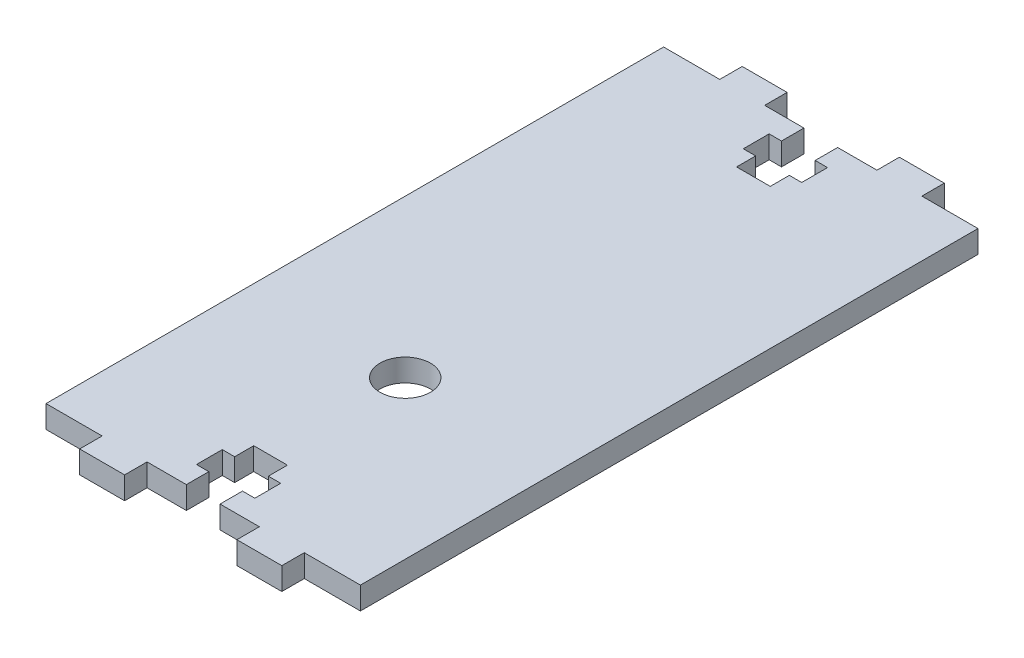
SolidWorks part; units mm, degrees
ref_plane "Front Plane" through (0, 0, 0) normal (0, 0, 1) x (1, 0, 0)
ref_plane "Top Plane" through (0, 0, 0) normal (0, 1, 0) x (1, 0, 0)
ref_plane "Right Plane" through (0, 0, 0) normal (1, 0, 0) x (0, 0, -1)
sketch "Sketch1" plane through (0, 0, 0) normal (0, 1, 0) x (1, 0, 0)
  line L0 (0, 27.2) -> (0, -27.2) construction
  line L7 (-14, -27.5) -> (-9, -27.5)
  line L8 (-14, -14.5) -> (-14, 14.5)
  line L9 (-14, 27.5) -> (-9, 27.5)
  line L10 (14, -27.5) -> (14, 27.5)
  line L11 (-14, -27.5) -> (14, 27.5) construction
  line L12 (-14, 27.5) -> (14, -27.5) construction
  line L18 (5, 27.5) -> (5, 29.5)
  line L19 (5, 29.5) -> (9, 29.5)
  line L20 (9, 27.5) -> (9, 29.5)
  line L21 (-14, 0) -> (14, 0) construction
  line L22 (9, 27.5) -> (14, 27.5)
  line L23 (-9, 27.5) -> (-9, 29.5)
  line L24 (-5, 29.5) -> (-9, 29.5)
  line L25 (-5, 27.5) -> (-5, 29.5)
  line L26 (-9, -27.5) -> (-9, -29.5)
  line L27 (-5, -29.5) -> (-9, -29.5)
  line L28 (-5, -27.5) -> (-5, -29.5)
  line L29 (9, -27.5) -> (9, -29.5)
  line L30 (5, -27.5) -> (5, -29.5)
  line L31 (5, -29.5) -> (9, -29.5)
  line L32 (-5, -27.5) -> (5, -27.5)
  line L33 (9, -27.5) -> (14, -27.5)
  line L34 (-5, 27.5) -> (5, 27.5)
  line L61 (-14, 14.5) -> (-14, 27.5)
  line L87 (-14, -14.5) -> (-14, -27.5)
  point P0 (0, 0)
  point P6 (0, 0)
  dimension "D3" = 55
  dimension "D5" = 2
  dimension "D6" = 4
  dimension "D7" = 5
extrude "Boss-Extrude1" add sketch "Sketch1" along normal blind 2
sketch "Sketch4" plane through (0, 2, 0) normal (0, 1, 0) x (1, 0, 0)
  line L0 (0, 27.5) -> (0, 20) construction
  line L1 (5, 27.5) -> (-5, 27.5) construction
  line L3 (-1.5, 23.2) -> (-2.6, 23.2)
  line L4 (-1.5, 21.5) -> (1.5, 21.5)
  line L5 (-1.5, 21.5) -> (-1.5, 23.2)
  line L6 (-1.5, 27.5) -> (1.5, 27.5)
  line L7 (1.5, 21.5) -> (1.5, 23.2)
  line L8 (-1.5, 21.5) -> (1.5, 27.5) construction
  line L9 (-1.5, 27.5) -> (1.5, 21.5) construction
  line L10 (1.5, 25.5) -> (2.6, 25.5)
  line L12 (1.5, 23.2) -> (2.6, 23.2)
  line L13 (2.6, 25.5) -> (2.6, 23.2)
  line L14 (-2.6, 25.5) -> (-2.6, 23.2)
  line L15 (-1.5, 25.5) -> (-2.6, 25.5)
  line L16 (-1.5, 25.5) -> (-1.5, 27.5)
  line L17 (1.5, 25.5) -> (1.5, 27.5)
  line L18 (14, 0) -> (0, 0) construction
  line L19 (14, -27.5) -> (14, 27.5) construction
  line L20 (1.5, -25.5) -> (1.5, -27.5)
  line L21 (-1.5, -27.5) -> (1.5, -27.5)
  line L22 (-1.5, -25.5) -> (-1.5, -27.5)
  line L23 (-1.5, -25.5) -> (-2.6, -25.5)
  line L24 (-2.6, -25.5) -> (-2.6, -23.2)
  line L25 (-1.5, -23.2) -> (-2.6, -23.2)
  line L26 (-1.5, -21.5) -> (-1.5, -23.2)
  line L27 (-1.5, -21.5) -> (1.5, -21.5)
  line L28 (1.5, -21.5) -> (1.5, -23.2)
  line L29 (1.5, -23.2) -> (2.6, -23.2)
  line L30 (2.6, -25.5) -> (2.6, -23.2)
  line L31 (1.5, -25.5) -> (2.6, -25.5)
  point P6 (0, 24.5)
  point P36 (0, 0)
  point P37 (0, 0)
  point P38 (0, 0)
  dimension "D1" = 3
  dimension "D2" = 6
  dimension "D3" = 2
  dimension "D4" = 2.3
  dimension "D5" = 1.1
extrude "Cut-Extrude2" cut sketch "Sketch4" against normal blind 2
sketch "Sketch5" plane through (0, 2, 0) normal (0, 1, 0) x (1, 0, 0)
  line L0 (0, 0) -> (0, -21.5) construction
  line L1 (1.5, -21.5) -> (-1.5, -21.5) construction
  line L2 (1.5, -27.5) -> (5, -27.5) construction
  circle A0 centre (0, -9.51) radius 2.25
  point P9 (3.25, -27.5)
  dimension "D1" = 4.5
  dimension "D2" = 17.99
extrude "Cut-Extrude4" cut sketch "Sketch5" against normal blind 2
